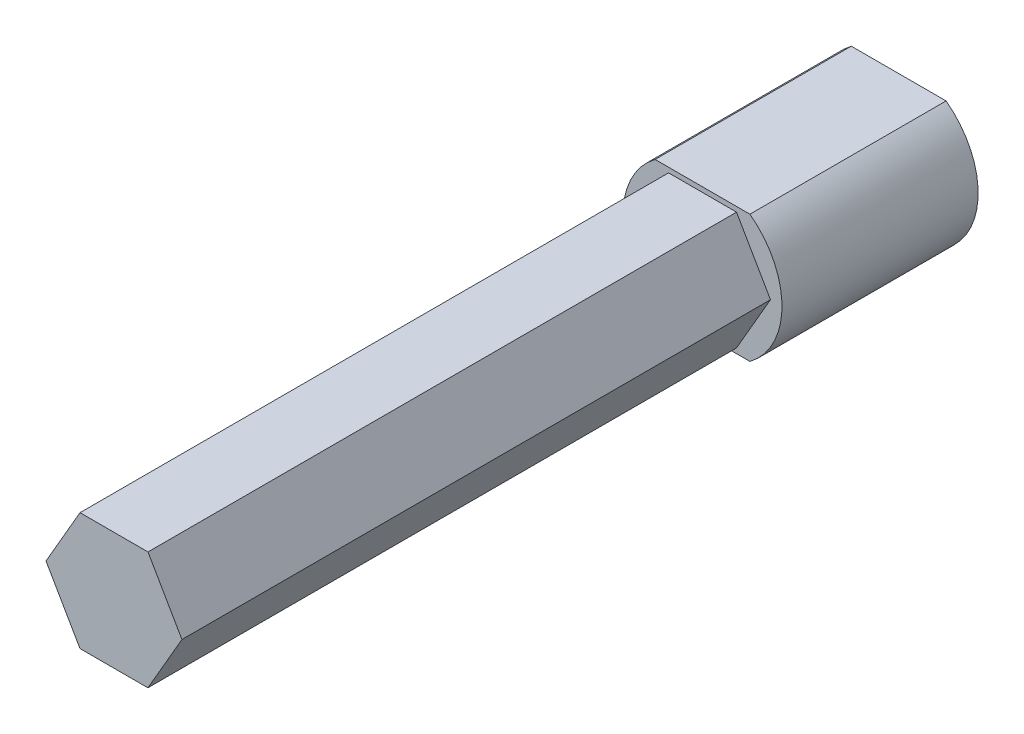
SolidWorks part; units mm, degrees
ref_plane "Front Plane" through (0, 0, 0) normal (0, 0, 1) x (1, 0, 0)
ref_plane "Top Plane" through (0, 0, 0) normal (0, 1, 0) x (1, 0, 0)
ref_plane "Right Plane" through (0, 0, 0) normal (1, 0, 0) x (0, 0, -1)
sketch "Sketch1" plane through (0, 0, 0) normal (0, 0, 1) x (1, 0, 0)
  line L0 (-2.4166, 3.25) -> (2.4166, 3.25)
  line L1 (-2.4166, -3.25) -> (2.4166, -3.25)
  arc A0 (-2.4166, 3.25) -> (-2.4166, -3.25) centre (0, 0) ccw
  arc A2 (2.4166, -3.25) -> (2.4166, 3.25) centre (0, 0) ccw
  dimension "D1" = 8.1
  dimension "D3" = 6.5
extrude "Boss-Extrude2" add sketch "Sketch1" along normal blind 10
sketch "Sketch3" plane through (0, 0, 0) normal (0, 0, -1) x (-1, 0, 0)
  line L2 (2.4166, 3.25) -> (-2.4166, 3.25)
  line L3 (-2.4166, -3.25) -> (2.4166, -3.25)
  line L4 (2.4166, 3.25) -> (-2.4166, 3.25)
  line L5 (-2.4166, -3.25) -> (2.4166, -3.25)
  line L6 (2.2091, 2.65) -> (-2.2091, 2.65)
  line L7 (-2.2091, -2.65) -> (2.2091, -2.65)
  arc A2 (2.4166, -3.25) -> (2.4166, 3.25) centre (0, 0) ccw
  arc A3 (-2.4166, 3.25) -> (-2.4166, -3.25) centre (0, 0) ccw
  arc A4 (2.4166, -3.25) -> (2.4166, 3.25) centre (0, 0) ccw
  arc A5 (-2.4166, 3.25) -> (-2.4166, -3.25) centre (0, 0) ccw
  arc A6 (-2.2091, 2.65) -> (-2.2091, -2.65) centre (0, 0) ccw
  arc A7 (2.2091, -2.65) -> (2.2091, 2.65) centre (0, 0) ccw
  dimension "D1" = 0
  dimension "D3" = 0.6
sketch "Sketch4" plane through (0, 0, 10) normal (0, 0, 1) x (1, 0, 0)
  line L1 (1.7303, -3.001) -> (3.4641, -0.0021)
  line L2 (3.4641, -0.0021) -> (1.7339, 2.999)
  line L3 (1.7339, 2.999) -> (-1.7303, 3.001)
  line L4 (-1.7303, 3.001) -> (-3.4641, 0.0021)
  line L5 (-3.4641, 0.0021) -> (-1.7339, -2.999)
  line L6 (-1.7339, -2.999) -> (1.7303, -3.001)
  circle A0 centre (0, 0) radius 3 construction
  dimension "D1" = 6
extrude "Boss-Extrude3" add sketch "Sketch4" along normal blind 30
extrude "Cut-Extrude1" cut sketch "Sketch3" against normal blind 5 contours L6 A6 L7 A7
